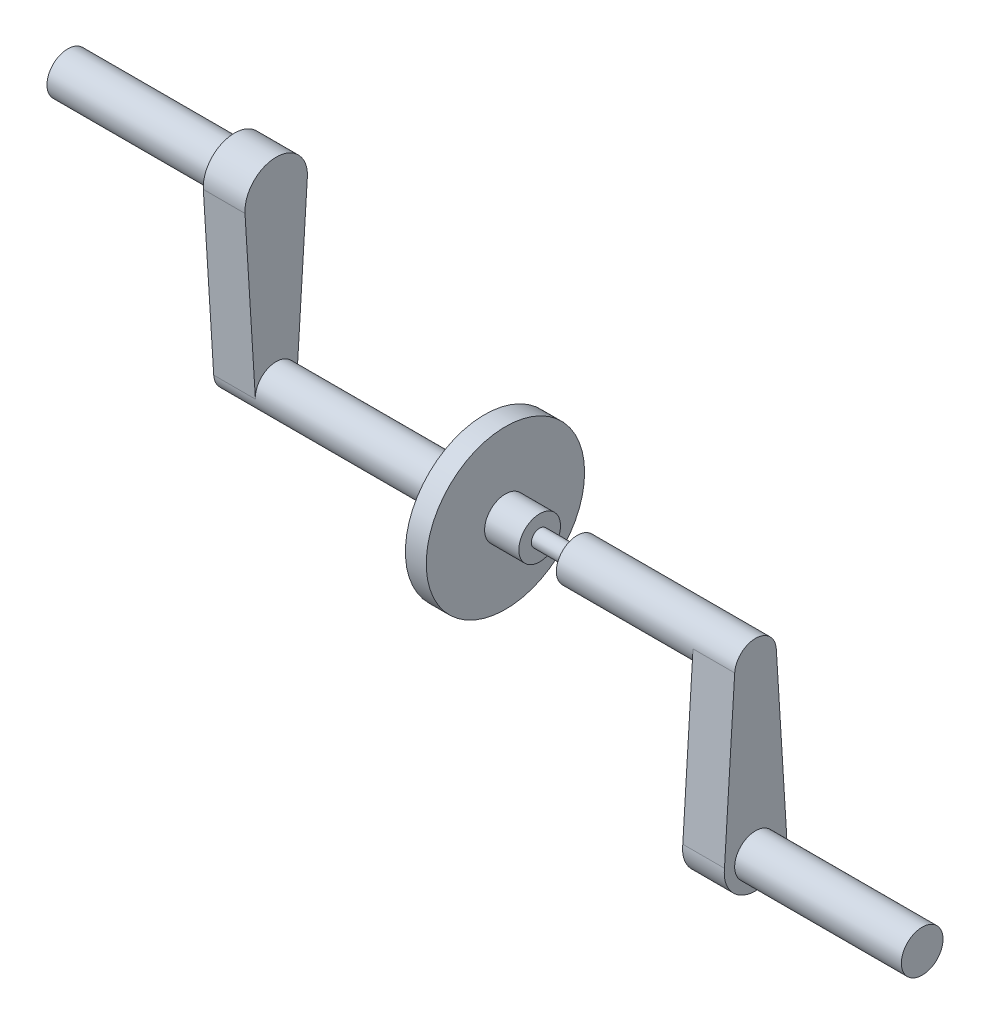
SolidWorks part; units mm, degrees
ref_plane "Alzado" through (0, 0, 0) normal (0, 0, 1) x (1, 0, 0)
ref_plane "Planta" through (0, 0, 0) normal (0, 1, 0) x (1, 0, 0)
ref_plane "Vista lateral" through (0, 0, 0) normal (1, 0, 0) x (0, 0, -1)
sketch "Croquis1" plane through (0, 0, 0) normal (1, 0, 0) x (0, 0, -1)
  circle A0 centre (0, 0) radius 38
  dimension "D1" = 76
extrude "Saliente-Extruir2" add sketch "Croquis1" along normal mid plane 10
sketch "Croquis2" plane through (5, 0, 0) normal (1, 0, 0) x (0, 0, -1)
  circle A0 centre (0, 0) radius 10
  dimension "D1" = 20
extrude "Saliente-Extruir3" add sketch "Croquis2" along normal blind 100
sketch "Croquis3" plane through (105, 0, 0) normal (1, 0, 0) x (0, 0, -1)
  line L0 (-9.9807, 0.6214) -> (-14.8842, -78.1395)
  line L1 (9.9807, 0.6214) -> (14.8842, -78.1395)
  line L2 (14.8842, -78.1395) -> (15, -80) construction
  line L3 (-14.8842, -78.1395) -> (-15, -80) construction
  arc A0 (-14.8842, -78.1395) -> (14.8842, -78.1395) centre (0, -80) ccw
  circle A1 centre (0, 0) radius 10 construction
  arc A2 (9.9807, 0.6214) -> (-9.9807, 0.6214) centre (0, 0) ccw
  arc A3 (-9.9807, 0.6214) -> (9.9807, 0.6214) centre (0, 0) ccw construction
  arc A4 (14.8842, -78.1395) -> (-14.8842, -78.1395) centre (0, -80) ccw construction
  dimension "D1" = 30
  dimension "D2" = 80
extrude "Saliente-Extruir4" add sketch "Croquis3" along normal blind 20
sketch "Croquis4" plane through (125, 0, 0) normal (1, 0, 0) x (0, 0, -1)
  circle A0 centre (0, -80) radius 10
  dimension "D1" = 20
extrude "Saliente-Extruir5" add sketch "Croquis4" along normal blind 80
mirror "Simetría1" about plane through (0, 0, 0) normal (1, 0, 0) of "Saliente-Extruir3"
sketch "Croquis5" plane through (-105, 0, 0) normal (-1, 0, 0) x (0, 0, 1)
  line L0 (-14.8842, 78.1395) -> (-9.9807, -0.6214)
  line L1 (14.9707, 79.0625) -> (9.9804, -0.625)
  line L2 (-15, 80) -> (-14.8842, 78.1395) construction
  arc A0 (14.9707, 79.0625) -> (-14.8842, 78.1395) centre (0, 80) ccw
  circle A1 centre (0, 0) radius 10 construction
  arc A2 (-9.9807, -0.6214) -> (9.9804, -0.625) centre (0, 0) ccw
  arc A3 (-14.8842, 78.1395) -> (14.9707, 79.0625) centre (0, 80) ccw construction
  arc A4 (9.9804, -0.625) -> (-9.9807, -0.6214) centre (0, 0) ccw construction
  dimension "D1" = 30
  dimension "D2" = 80
extrude "Saliente-Extruir6" add sketch "Croquis5" along normal blind 20
sketch "Croquis6" plane through (-125, 0, 0) normal (-1, 0, 0) x (0, 0, 1)
  circle A0 centre (0, 80) radius 10
  dimension "D1" = 20
extrude "Saliente-Extruir7" add sketch "Croquis6" along normal blind 80
ref_plane "Plano1" through (39.44, 0, 0) normal (1, 0, 0) x (0, 0, -1)
sketch "Croquis7" plane through (39.44, 0, 0) normal (1, 0, 0) x (0, 0, -1)
  circle A0 centre (0, 0) radius 4
  circle A1 centre (0, 0) radius 10
  arc A2 (9.9807, 0.6214) -> (-9.9807, 0.6214) centre (0, 0) ccw construction
  dimension "D1" = 8
extrude "Cortar-Extruir1" cut sketch "Croquis7" against normal blind 18
